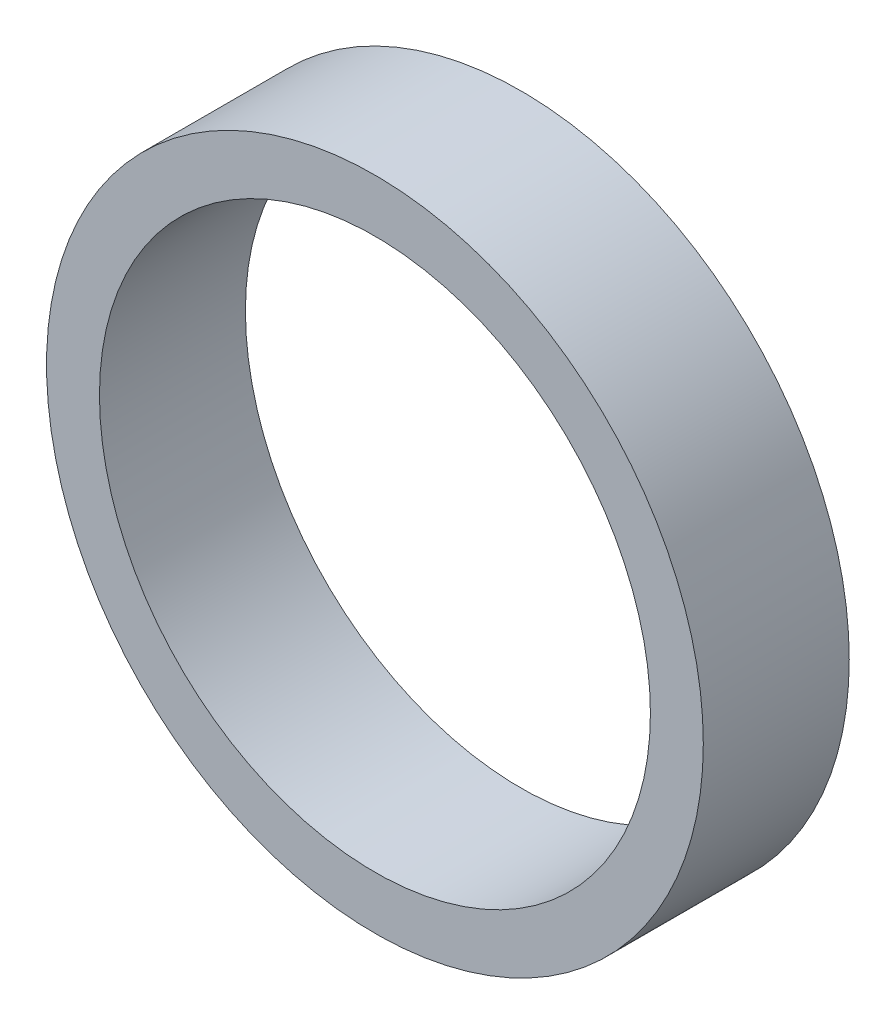
SolidWorks part; units mm, degrees
ref_plane "Front Plane" through (0, 0, 0) normal (1, 0, 0) x (0, 1, 0)
ref_plane "Top Plane" through (0, 0, 0) normal (0, 0, 1) x (0, 1, 0)
ref_plane "Right Plane" through (0, 0, 0) normal (0, 1, 0) x (-1, 0, 0)
sketch "Sketch1" plane through (0, 0, 0) normal (0, 0, 1) x (0, 1, 0)
  circle A0 centre (0, 0) radius 9
  dimension "D1" = 18
extrude "Boss-Extrude1" add sketch "Sketch1" along normal blind 4 contours A0
sketch "Sketch2" plane through (0, 0, 4) normal (0, 0, 1) x (1, 0, 0)
  circle A0 centre (0, 0) radius 7.55
  dimension "D1" = 15.1
extrude "Cut-Extrude1" cut sketch "Sketch2" against normal blind 4
